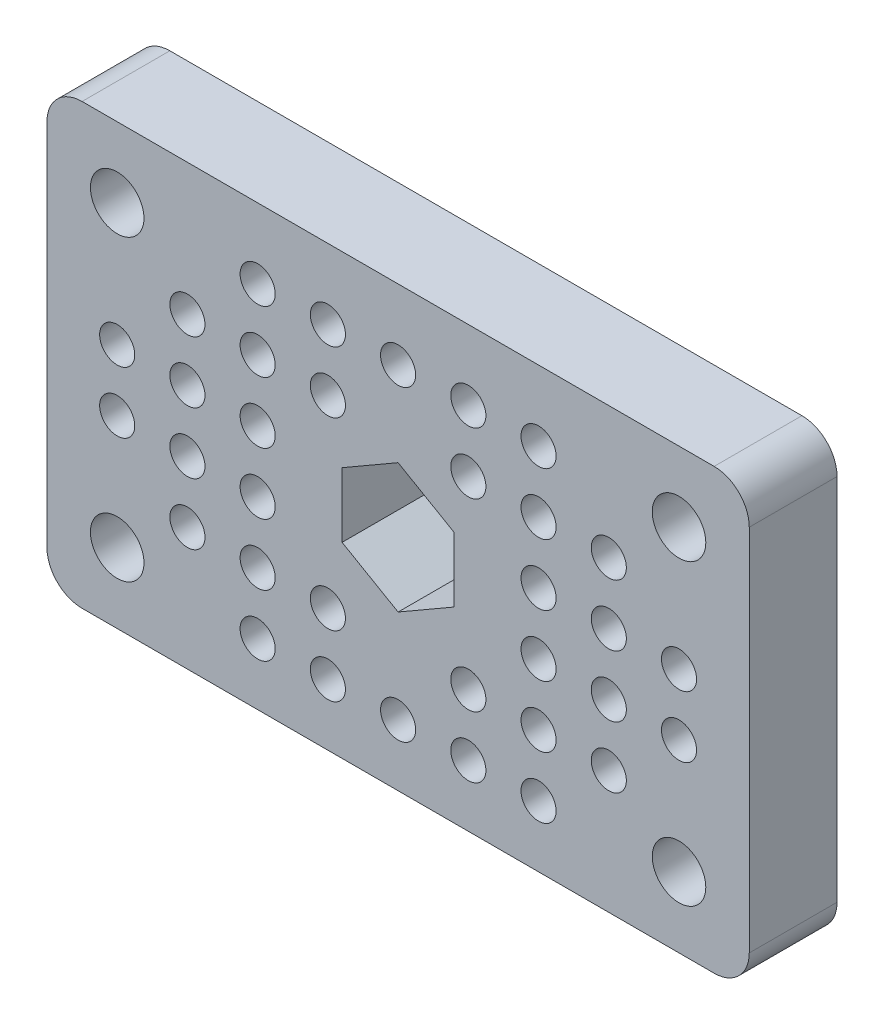
SolidWorks part; units mm, degrees
ref_plane "Front Plane" through (0, 0, 0) normal (0, 0, 1) x (1, 0, 0)
ref_plane "Top Plane" through (0, 0, 0) normal (0, 1, 0) x (1, 0, 0)
ref_plane "Right Plane" through (0, 0, 0) normal (1, 0, 0) x (0, 0, -1)
sketch "Model" plane through (0, 0, 0) normal (0, 0, 1) x (1, 0, 0)
  line L0 (6.38, -3.6835) -> (6.38, 3.6835)
  line L1 (6.38, 3.6835) -> (0, 7.367)
  line L2 (0, 7.367) -> (-6.38, 3.6835)
  line L3 (-6.38, 3.6835) -> (-6.38, -3.6835)
  line L4 (-6.38, -3.6835) -> (0, -7.367)
  line L5 (0, -7.367) -> (6.38, -3.6835)
  line L6 (-36, -25) -> (36, -25)
  line L7 (-40, 21) -> (-40, -21)
  line L8 (36, 25) -> (-36, 25)
  line L9 (40, -21) -> (40, 21)
  circle A0 centre (-32, 17) radius 3.05
  circle A1 centre (32, -17) radius 3.05
  circle A2 centre (32, 17) radius 3.05
  circle A3 centre (-32, -17) radius 3.05
  circle A4 centre (-16, 17) radius 2
  circle A5 centre (16, 10) radius 2
  circle A6 centre (24, 10) radius 2
  circle A7 centre (-16, 3) radius 2
  circle A8 centre (-32, -4) radius 2
  circle A9 centre (32, 3) radius 2
  circle A10 centre (-16, -4) radius 2
  circle A11 centre (24, 3) radius 2
  circle A12 centre (16, 3) radius 2
  circle A13 centre (-16, 10) radius 2
  circle A14 centre (-8, 10) radius 2
  circle A15 centre (-32, 3) radius 2
  circle A16 centre (8, 10) radius 2
  circle A17 centre (16, 17) radius 2
  circle A18 centre (8, 17) radius 2
  circle A19 centre (0, 17) radius 2
  circle A20 centre (-8, 17) radius 2
  circle A21 centre (-16, -18) radius 2
  circle A22 centre (-8, -18) radius 2
  circle A23 centre (0, -18) radius 2
  circle A24 centre (8, -18) radius 2
  circle A25 centre (-24, -11) radius 2
  circle A26 centre (-24, -4) radius 2
  circle A27 centre (-24, 3) radius 2
  circle A28 centre (-24, 10) radius 2
  circle A29 centre (16, -18) radius 2
  circle A30 centre (-16, -11) radius 2
  circle A31 centre (24, -4) radius 2
  circle A32 centre (16, -4) radius 2
  circle A33 centre (32, -4) radius 2
  circle A34 centre (-8, -11) radius 2
  circle A35 centre (8, -11) radius 2
  circle A36 centre (16, -11) radius 2
  circle A37 centre (24, -11) radius 2
  arc A38 (-40, -21) -> (-36, -25) centre (-36, -21) ccw
  arc A39 (-36, 25) -> (-40, 21) centre (-36, 21) ccw
  arc A40 (40, 21) -> (36, 25) centre (36, 21) ccw
  arc A41 (36, -25) -> (40, -21) centre (36, -21) ccw
extrude "Boss-Extrude1" add sketch "Model" along normal blind 10
sketch "Sketch2" plane through (0, 0, 10) normal (0, 0, 1) x (1, 0, 0)
  text T0 "Copyright © Adarsh Belavatagi and Manikanta Pujar 2018.\r\nThis documentation describes Open Hardware and is licensed under the CERN OHL v. 1.2.\r\nYou may redistribute and modify this documentation under the terms of the CERN OHL v.1.2.\r\n(http://ohwr.org/cernohl). This documentation is distributed WITHOUT ANY EXPRESS OR\r\nIMPLIED WARRANTY, INCLUDING OF MERCHANTABILITY, SATISFACTORY QUALITY AND FITNESS FOR A PARTICULAR PURPOSE.\r\nPlease see the CERN OHL v.1.2 for applicable conditions\r\n\r\nThe full text of the license is available in LICENSE.txt(https://github.com/AdarshBelavatagi/Maudslay/blob/master/LICENSE.txt)"
